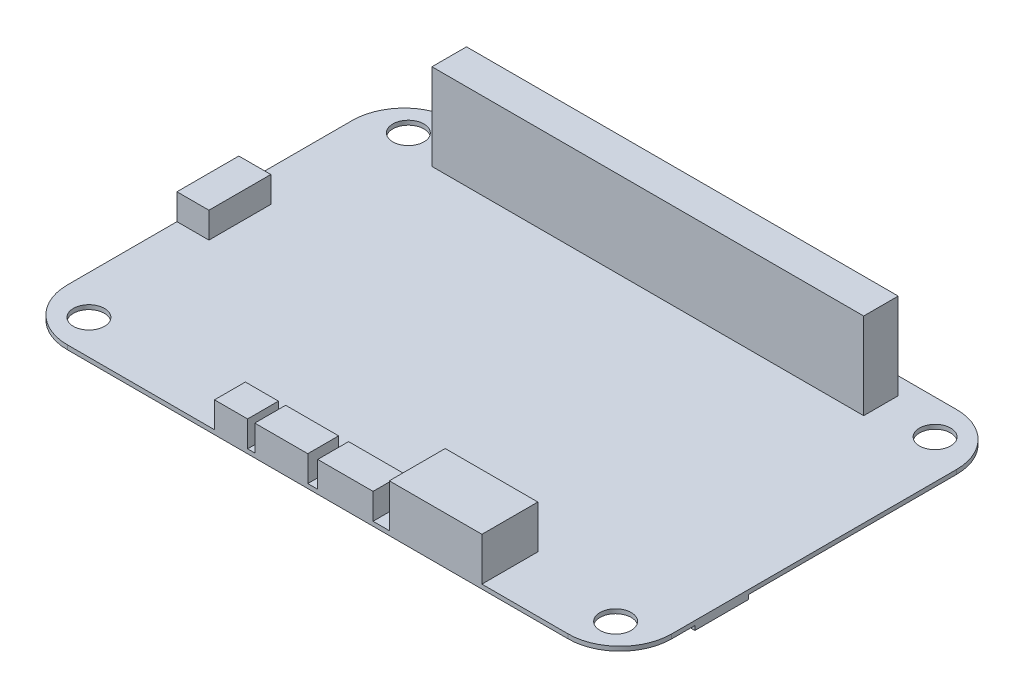
SolidWorks part; units mm, degrees
ref_plane "前视基准面" through (0, 0, 0) normal (0, 0, 1) x (1, 0, 0)
ref_plane "上视基准面" through (0, 0, 0) normal (0, 1, 0) x (1, 0, 0)
ref_plane "右视基准面" through (0, 0, 0) normal (1, 0, 0) x (0, 0, -1)
other "Configuration Table"
sketch "草图1" plane through (0, 0, 0) normal (0, 1, 0) x (1, 0, 0)
  line L0 (-70.1064, 0) -> (82.234, 0) construction
  line L1 (0, 80.1064) -> (0, -104.3617) construction
  line L3 (-35, 22.5) -> (35, 22.5)
  line L4 (-35, 22.5) -> (-35, -22.5)
  line L5 (-35, -22.5) -> (35, -22.5)
  line L6 (35, 22.5) -> (35, -22.5)
  dimension "D1" = 70
  dimension "D2" = 45
extrude "凸台-拉伸1" add sketch "草图1" along normal blind 0.5
fillet "圆角1" radius 6 4 edges at (-35, 0.25, 22.5) (-35, 0.25, -22.5) (35, 0.25, -22.5) (35, 0.25, 22.5)
sketch "草图3" plane through (0, 0.5, 0) normal (0, 1, 0) x (1, 0, 0)
  line L0 (-47.2021, 0) -> (45.6803, 0) construction
  line L1 (0, 28.3998) -> (0, -28.8416) construction
  circle A0 centre (30.5, 18.5) radius 1.8
  circle A1 centre (30.5, -18.5) radius 1.8
  circle A2 centre (-30.5, -18.5) radius 1.8
  circle A3 centre (-30.5, 18.5) radius 1.8
  dimension "D1" = 3.6
  dimension "D2" = 61
  dimension "D3" = 37
extrude "切除-拉伸1" cut sketch "草图3" against normal blind 1
sketch "草图4" plane through (0, 0.5, 0) normal (0, 1, 0) x (1, 0, 0)
  line L0 (0, 35.5293) -> (0, -33.8022) construction
  line L1 (-25.7705, 20.5) -> (24.2295, 20.5)
  line L2 (-25.7705, 20.5) -> (-25.7705, 16.5)
  line L3 (-25.7705, 16.5) -> (24.2295, 16.5)
  line L4 (24.2295, 20.5) -> (24.2295, 16.5)
  line L5 (30.5, 18.5) -> (38.0521, 18.5) construction
  dimension "D1" = 4
  dimension "D2" = 50
extrude "凸台-拉伸2" add sketch "草图4" along normal blind 10
sketch "草图5" plane through (0, 0, 0) normal (0, -1, 0) x (1, 0, 0)
  line L0 (29, -22.5) -> (-29, -22.5) construction
  line L1 (-25.2579, -22.5) -> (-15.734, -22.5)
  line L2 (-25.2579, -22.5) -> (-25.2579, -20.2505)
  line L3 (-25.2579, -20.2505) -> (-15.734, -20.2505)
  line L4 (-15.734, -22.5) -> (-15.734, -20.2505)
  line L5 (35, 16.5) -> (35, -16.5) construction
  line L6 (-12.4449, -22.5) -> (-7.8793, -22.5)
  line L7 (-12.4449, -22.5) -> (-12.4449, -17.9432)
  line L8 (-12.4449, -17.9432) -> (-7.8793, -17.9432)
  line L9 (-7.8793, -22.5) -> (-7.8793, -17.9432)
  line L10 (-4.4919, -22.5) -> (13.4758, -22.5)
  line L11 (-4.4919, -22.5) -> (-4.4919, -17.9432)
  line L12 (-4.4919, -17.9432) -> (13.4758, -17.9432)
  line L13 (13.4758, -22.5) -> (13.4758, -17.9432)
  line L14 (15.5377, -22.5) -> (28.1544, -22.5)
  line L15 (15.5377, -22.5) -> (15.5377, -17.9432)
  line L16 (15.5377, -17.9432) -> (28.1544, -17.9432)
  line L17 (28.1544, -22.5) -> (28.1544, -17.9432)
  line L18 (-28.3998, -0.3191) -> (-16.3231, -0.3191)
  line L19 (-28.3998, -0.3191) -> (-28.3998, -12.7394)
  line L20 (-28.3998, -12.7394) -> (-16.3231, -12.7394)
  line L21 (-16.3231, -0.3191) -> (-16.3231, -12.7394)
  line L22 (35, 13.8194) -> (31.5908, 13.8194)
  line L23 (35, 13.8194) -> (35, 7.5847)
  line L24 (35, 7.5847) -> (31.5908, 7.5847)
  line L25 (31.5908, 13.8194) -> (31.5908, 7.5847)
extrude "凸台-拉伸3" add sketch "草图5" along normal blind 0.5
sketch "草图6" plane through (0, 0.5, 0) normal (0, 1, 0) x (1, 0, 0)
  line L0 (-29, -22.5) -> (29, -22.5) construction
  line L6 (8.2889, -22.5) -> (19.0175, -22.5)
  line L7 (8.2889, -22.5) -> (8.2889, -16.0249)
  line L8 (8.2889, -16.0249) -> (19.0175, -16.0249)
  line L9 (19.0175, -22.5) -> (19.0175, -16.0249)
extrude "凸台-拉伸4" add sketch "草图6" along normal blind 5
sketch "草图7" plane through (0, 0.5, 0) normal (0, 1, 0) x (1, 0, 0)
  line L0 (-29, -22.5) -> (8.2889, -22.5) construction
  line L1 (6.4065, -22.5) -> (0, -22.5)
  line L2 (6.4065, -22.5) -> (6.4065, -18.925)
  line L3 (6.4065, -18.925) -> (0, -18.925)
  line L4 (0, -22.5) -> (0, -18.925)
  line L5 (-35, 16.5) -> (-35, -16.5) construction
  line L6 (-1.1537, -22.5) -> (-7.2902, -22.5)
  line L7 (-1.1537, -22.5) -> (-1.1537, -18.925)
  line L8 (-1.1537, -18.925) -> (-7.2902, -18.925)
  line L9 (-7.2902, -22.5) -> (-7.2902, -18.925)
  line L10 (-8.1248, -22.5) -> (-11.9539, -22.5)
  line L11 (-8.1248, -22.5) -> (-8.1248, -18.925)
  line L12 (-8.1248, -18.925) -> (-11.9539, -18.925)
  line L13 (-11.9539, -22.5) -> (-11.9539, -18.925)
  line L14 (-35, 3.3628) -> (-31.2963, 3.3628)
  line L15 (-35, 3.3628) -> (-35, -3.8046)
  line L16 (-35, -3.8046) -> (-31.2963, -3.8046)
  line L17 (-31.2963, 3.3628) -> (-31.2963, -3.8046)
extrude "凸台-拉伸5" add sketch "草图7" along normal blind 3
